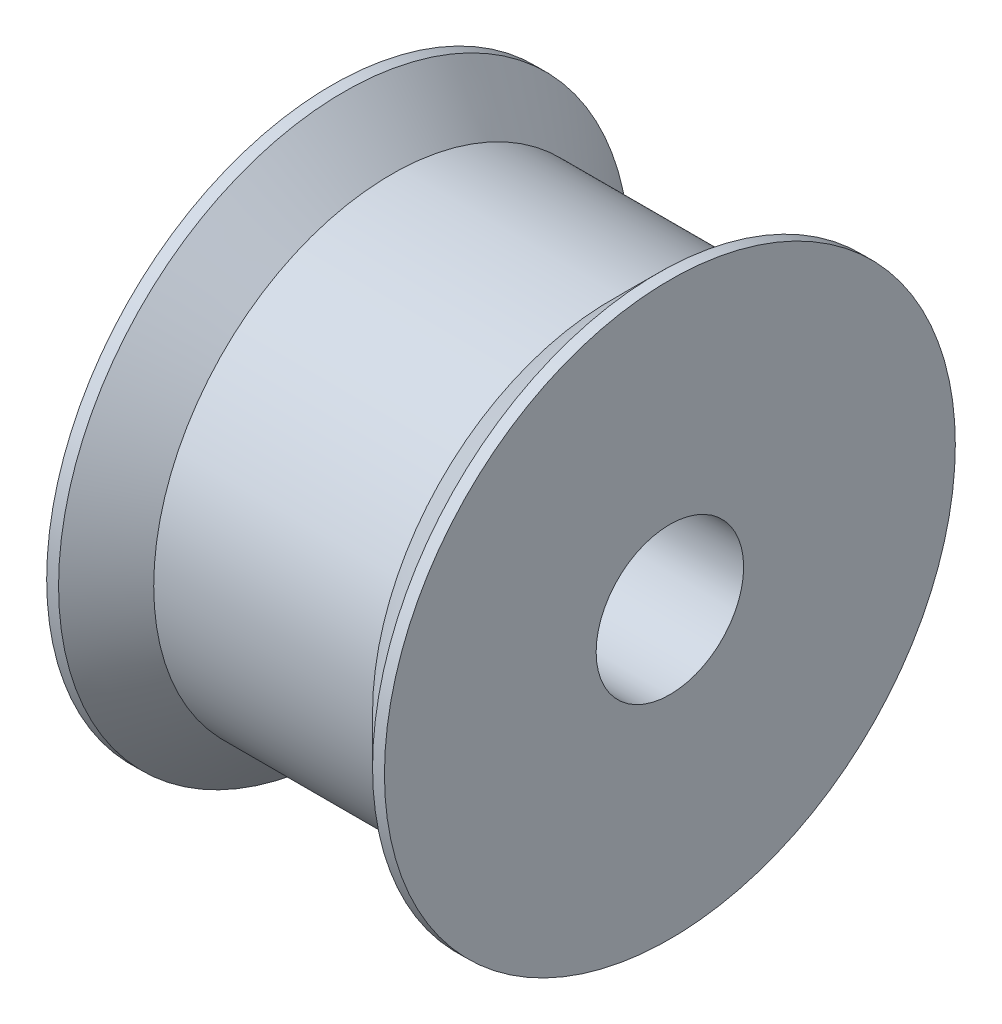
SolidWorks part; units mm, degrees
ref_plane "Front Plane" through (0, 0, 0) normal (0, 0, 1) x (1, 0, 0)
ref_plane "Top Plane" through (0, 0, 0) normal (0, 1, 0) x (1, 0, 0)
ref_plane "Right Plane" through (0, 0, 0) normal (1, 0, 0) x (0, 0, -1)
sketch "Sketch2" plane through (0, 0, 0) normal (0, 1, 0) x (1, 0, 0)
  line L0 (-7.1, 12) -> (-6.6, 12)
  line L1 (-6.6, 12) -> (-4.6, 10)
  line L2 (-4.6, 10) -> (4.6, 10)
  line L3 (4.6, 10) -> (6.6, 12)
  line L4 (6.6, 12) -> (7.1, 12)
  line L5 (7.1, 12) -> (7.1, 0)
  line L6 (-7.1, 12) -> (-7.1, 0)
  line L7 (-54.6936, 0) -> (47.2254, 0) construction
  line L8 (0, -23.2469) -> (0, 34.557) construction
  line L9 (7.1, 0) -> (-7.1, 0)
  point P16 (0, 10)
  dimension "D1" = 12
  dimension "D2" = 2.5
  dimension "D3" = 9.2
  dimension "D4" = 10
revolve "Revolve1" add sketch "Sketch2" angle 360 about L9
sketch "Sketch3" plane through (-7.1, 0, 0) normal (-1, 0, 0) x (0, 0, 1)
  circle A0 centre (0, 0) radius 3.1
  dimension "D1" = 6.2
extrude "Cut-Extrude1" cut sketch "Sketch3" against normal up to surface (14.2 mm away) up to face at (7.1, 0, -12)
sketch "Sketch5" plane through (-7.1, 0, 0) normal (-1, 0, 0) x (0, 0, 1)
  circle A0 centre (0, 0) radius 3.1
  circle A1 centre (0, 0) radius 12
  circle A2 centre (0, 0) radius 12 construction
  circle A3 centre (0, 0) radius 3.1 construction
